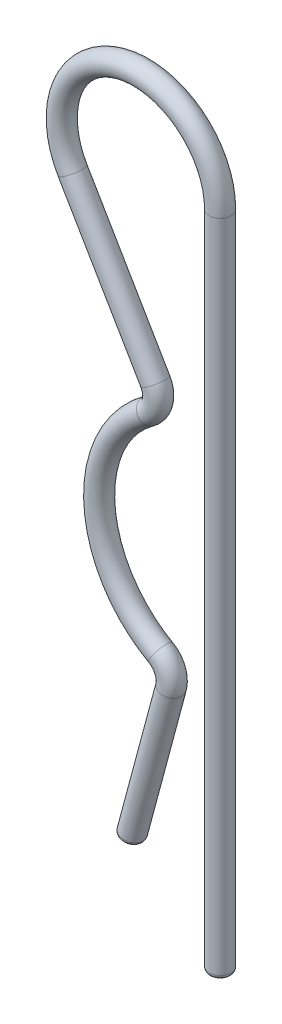
SolidWorks part; units mm, degrees
material "1.4000 (X6Cr13)"
ref_plane "Front Plane" through (0, 0, 0) normal (0, 0, 1) x (1, 0, 0)
ref_plane "Top Plane" through (0, 0, 0) normal (0, 1, 0) x (1, 0, 0)
ref_plane "Right Plane" through (0, 0, 0) normal (1, 0, 0) x (0, 0, -1)
sketch "Sketch1" plane through (0, 0, 0) normal (0, 0, 1) x (1, 0, 0)
  line L0 (0, -80) -> (0, 70)
  line L1 (-33.5329, 60.9044) -> (-14.7579, 28.8417)
  line L2 (-11.1616, -29.5877) -> (-20.2203, -63.3951)
  circle A1 centre (0, 0) radius 27.5 construction
  arc A2 (0, 70) -> (-33.5329, 60.9044) centre (-18, 70) ccw
  arc A3 (-16.1384, 22.2666) -> (-13.5311, -23.9408) centre (0, 0) ccw
  arc A4 (-13.5311, -23.9408) -> (-11.1616, -29.5877) centre (-15.9913, -28.2936) cw
  arc A5 (-14.7579, 28.8417) -> (-16.1384, 22.2666) centre (-19.0726, 26.3151) cw
  dimension "D1" = 150
  dimension "D4" = 5
  dimension "D5" = 55
  dimension "D7" = 55
  dimension "D9" = 37.1553
  dimension "D6" = 27.5
  dimension "D10" = 18
  dimension "D2" = 80
  dimension "D3" = 15
  dimension "D8" = 35
ref_plane "Plane1" through (0, -80, 0) normal (0, 1, 0) x (1, 0, 0)
sketch "Sketch2" plane through (0, -80, 0) normal (0, 1, 0) x (1, 0, 0)
  line L0 (-27.5, 0) -> (27.5, 0) construction
  circle A0 centre (0, 0) radius 2.5
  dimension "D1" = 5
sweep "Sweep1" add profiles "Sketch2" path "Sketch1"
fillet "Fillet1" radius 1 2 edges at (0, -80, 2.5) (-20.2203, -63.3951, 2.5)
